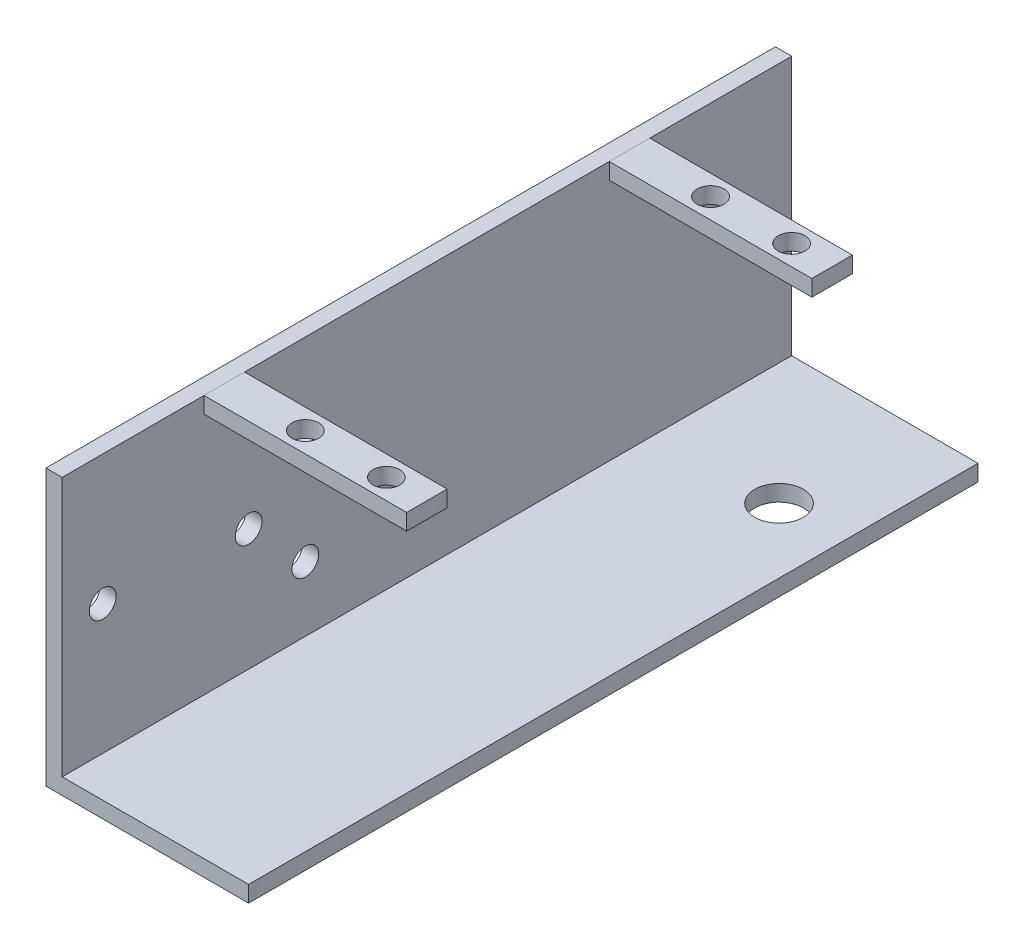
SolidWorks part; units mm, degrees
ref_plane "前视基准面" through (0, 0, 0) normal (0, 0, 1) x (1, 0, 0)
ref_plane "上视基准面" through (0, 0, 0) normal (0, 1, 0) x (1, 0, 0)
ref_plane "右视基准面" through (0, 0, 0) normal (1, 0, 0) x (0, 0, -1)
sketch "草图1" plane through (0, 0, 0) normal (0, 1, 0) x (1, 0, 0)
  line L1 (-12.5, -45) -> (12.5, -45)
  line L2 (-12.5, -45) -> (-12.5, 45)
  line L3 (-12.5, 45) -> (12.5, 45)
  line L4 (12.5, -45) -> (12.5, 45)
  line L5 (-12.5, -45) -> (12.5, 45) construction
  line L6 (-12.5, 45) -> (12.5, -45) construction
  point P1 (0, 0)
  dimension "D1" = 90
  dimension "D2" = 25
extrude "凸台-拉伸1" add sketch "草图1" along normal blind 2
sketch "草图3" plane through (0, 2, 0) normal (0, 1, 0) x (1, 0, 0)
  line L0 (-12.5, -45) -> (12.5, -45) construction
  line L1 (-12.5, 45) -> (-10.5, 45)
  line L2 (-12.5, 45) -> (-12.5, -45)
  line L3 (-12.5, -45) -> (-10.5, -45)
  line L4 (-10.5, 45) -> (-10.5, -45)
  dimension "D1" = 2
extrude "凸台-拉伸2" add sketch "草图3" along normal blind 32
sketch "草图4" plane through (-10.5, 0, 0) normal (1, 0, 0) x (0, 0, -1)
  line L0 (0, 34) -> (0, 2) construction
  line L1 (-45, 34) -> (45, 34) construction
  line L2 (-45, 2) -> (45, 2) construction
  line L3 (-22.5, 32) -> (22.5, 32) construction
  line L4 (22.5, 34) -> (27.5, 34)
  line L5 (-22.5, 32) -> (-27.5, 32)
  line L6 (-22.5, 32) -> (-22.5, 34)
  line L7 (-22.5, 34) -> (-27.5, 34)
  line L8 (-27.5, 32) -> (-27.5, 34)
  line L9 (27.5, 32) -> (27.5, 34)
  line L10 (22.5, 32) -> (27.5, 32)
  line L11 (22.5, 32) -> (22.5, 34)
  line L12 (-45, 2) -> (45, 2) construction
  dimension "D1" = 45
  dimension "D2" = 5
  dimension "D3" = 2
  dimension "D4" = 30
extrude "凸台-拉伸3" add sketch "草图4" along normal blind 25 separate body
sketch "草图5" plane through (0, 34, 0) normal (0, 1, 0) x (1, 0, 0)
  line L0 (-10.5, -25) -> (14.5, -25) construction
  line L1 (-10.5, -22.5) -> (-10.5, -27.5) construction
  line L2 (14.5, -22.5) -> (14.5, -27.5) construction
  line L3 (-12.5, 0) -> (-10.5, 0) construction
  line L4 (-12.5, 45) -> (-12.5, -45) construction
  line L5 (-10.5, -45) -> (-10.5, 45) construction
  circle A0 centre (-0.5, -25) radius 1.65
  circle A1 centre (9.5, -25) radius 1.65
  circle A2 centre (9.5, 25) radius 1.65
  circle A3 centre (-0.5, 25) radius 1.65
  dimension "D1" = 3.3
  dimension "D2" = 3.3
  dimension "D3" = 10
  dimension "D4" = 10
extrude "切除-拉伸2" cut sketch "草图5" against normal up to next (2 mm away)
sketch "草图6" plane through (-12.5, 0, 0) normal (-1, 0, 0) x (0, 0, 1)
  line L0 (-45, 17) -> (45, 17) construction
  line L1 (-45, 34) -> (-45, 0) construction
  line L2 (45, 34) -> (45, 0) construction
  circle A0 centre (8, 17) radius 1.65
  circle A1 centre (22, 17) radius 1.65
  circle A2 centre (15, 10) radius 1.65
  circle A3 centre (15, 24) radius 1.65
  dimension "D1" = 3.3
  dimension "D3" = 7
  dimension "D4" = 3.3
  dimension "D7" = 3.3
  dimension "D2" = 30
  dimension "D5" = 14
  dimension "D6" = 37
extrude "切除-拉伸3" cut sketch "草图6" against normal blind 10
sketch "草图7" plane through (0, 0, 0) normal (0, -1, 0) x (-1, 0, 0)
  line L0 (-12.5, 45) -> (12.5, 45) construction
  line L1 (12.5, 45) -> (12.5, -45) construction
  circle A0 centre (-4.5, 28.45) radius 3
  dimension "D3" = 6
  dimension "D1" = 16.55
  dimension "D2" = 17
extrude "切除-拉伸4" cut sketch "草图7" against normal blind 10
sketch "草图8" plane through (-10.5, 0, 0) normal (1, 0, 0) x (0, 0, -1)
  line L0 (-45, 18) -> (45, 18) construction
  line L1 (-45, 34) -> (-45, 2) construction
  line L2 (45, 34) -> (45, 2) construction
  line L3 (0, 34) -> (0, 2) construction
  line L4 (-45, 34) -> (45, 34) construction
  line L5 (-45, 2) -> (45, 2) construction
  circle A0 centre (-40, 18) radius 1.65
  circle A1 centre (40, 18) radius 1.65
  point P16 (0, 0)
  point P17 (0, 0)
  dimension "D1" = 3.3
  dimension "D2" = 3.3
  dimension "D3" = 80
extrude "切除-拉伸5" cut sketch "草图8" against normal blind 10
